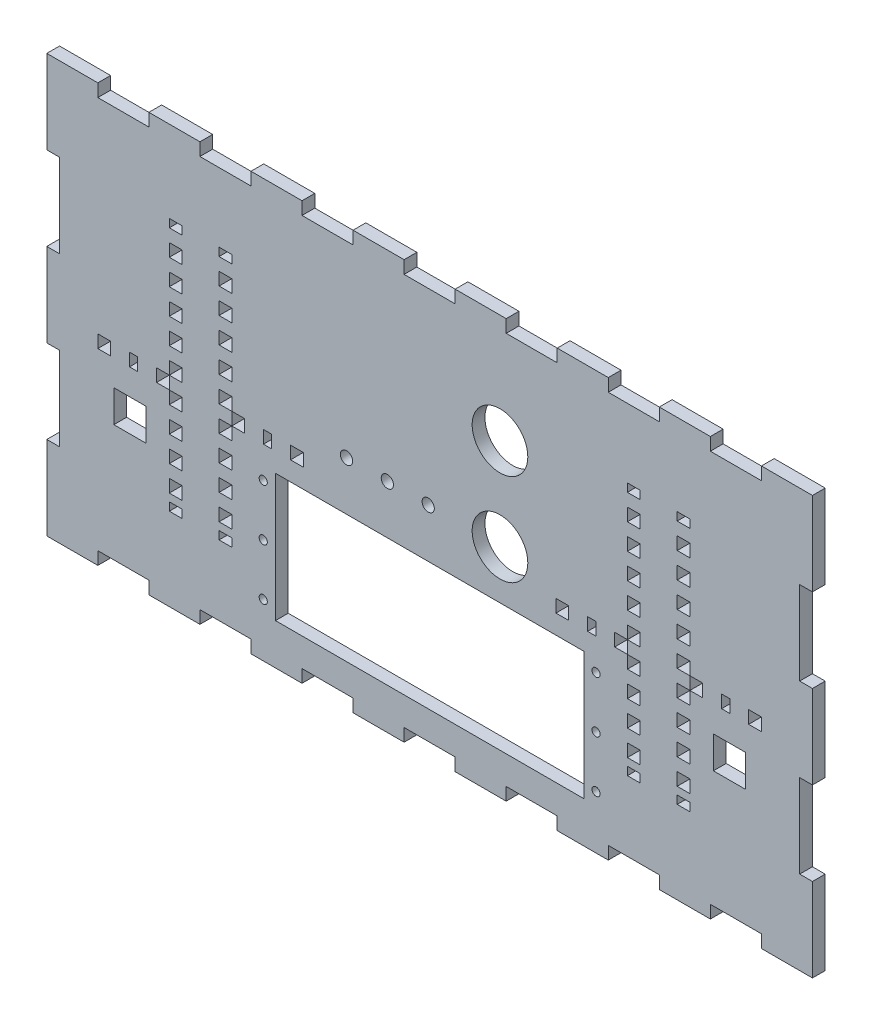
SolidWorks part; units mm, degrees
ref_plane "Front Plane" through (0, 0, 0) normal (0, 0, 1) x (1, 0, 0)
ref_plane "Top Plane" through (0, 0, 0) normal (0, 1, 0) x (1, 0, 0)
ref_plane "Right Plane" through (0, 0, 0) normal (1, 0, 0) x (0, 0, -1)
sketch "Sketch1" plane through (0, 0, 0) normal (0, 0, 1) x (1, 0, 0)
  line B0 (-76.708, -20.066) -> (76.708, -20.066)
  line B1 (76.708, -20.066) -> (76.708, -83.566)
  line B2 (-76.708, -83.566) -> (76.708, -83.566)
  line B3 (-76.708, -20.066) -> (-76.708, -83.566)
  line B4 (158.75, -4.191) -> (158.75, -10.541)
  line B5 (158.75, -4.191) -> (165.1, -4.191)
  line B6 (165.1, -4.191) -> (165.1, -10.541)
  line B7 (158.75, -10.541) -> (165.1, -10.541)
  line B8 (-158.75, -4.191) -> (-165.1, -4.191)
  line B9 (-158.75, -4.191) -> (-158.75, -10.541)
  line B10 (-158.75, -10.541) -> (-165.1, -10.541)
  line B11 (-165.1, -4.191) -> (-165.1, -10.541)
  line B12 (-123.19, 14.8272) -> (-123.19, 8.4772)
  line B13 (-123.19, 8.4772) -> (-129.54, 8.4772)
  line B14 (-129.54, 14.8272) -> (-129.54, 8.4772)
  line B15 (-123.19, 14.8272) -> (-129.54, 14.8272)
  line B16 (-123.19, 27.5273) -> (-123.19, 21.1773)
  line B17 (-123.19, 21.1773) -> (-129.54, 21.1773)
  line B18 (-129.54, 27.5273) -> (-129.54, 21.1773)
  line B19 (-123.19, 27.5273) -> (-129.54, 27.5273)
  line B20 (-123.19, 40.2272) -> (-123.19, 33.8772)
  line B21 (-123.19, 33.8772) -> (-129.54, 33.8772)
  line B22 (-129.54, 40.2272) -> (-129.54, 33.8772)
  line B23 (-123.19, 40.2272) -> (-129.54, 40.2272)
  line B24 (-145.288, -4.191) -> (-149.352, -4.191)
  line B25 (-145.288, -4.191) -> (-145.288, -10.541)
  line B26 (-145.288, -10.541) -> (-149.352, -10.541)
  line B27 (-149.352, -4.191) -> (-149.352, -10.541)
  line B28 (-123.19, -4.2227) -> (-129.54, -4.2227)
  line B29 (-129.54, -4.2227) -> (-129.54, -10.541)
  line B30 (-129.54, -10.541) -> (-135.89, -10.541)
  line B31 (-135.89, -10.541) -> (-135.89, -4.191)
  line B32 (-129.54, -4.191) -> (-135.89, -4.191)
  line B33 (-129.54, 2.1272) -> (-129.54, -4.191)
  line B34 (-123.19, 2.1272) -> (-129.54, 2.1272)
  line B35 (-123.19, 2.1272) -> (-123.19, -4.2227)
  line B36 (-123.19, -10.5728) -> (-129.54, -10.5728)
  line B37 (-123.19, -10.5728) -> (-123.19, -16.9228)
  line B38 (-123.19, -16.9228) -> (-129.54, -16.9228)
  line B39 (-129.54, -10.5728) -> (-129.54, -16.9228)
  line B40 (-123.19, -23.2727) -> (-123.19, -29.6228)
  line B41 (-123.19, -29.6228) -> (-129.54, -29.6228)
  line B42 (-129.54, -23.2727) -> (-129.54, -29.6228)
  line B43 (-123.19, -23.2727) -> (-129.54, -23.2727)
  line B44 (-123.19, -35.9727) -> (-123.19, -42.3227)
  line B45 (-123.19, -42.3227) -> (-129.54, -42.3227)
  line B46 (-129.54, -35.9727) -> (-129.54, -42.3227)
  line B47 (-123.19, -35.9727) -> (-129.54, -35.9727)
  line B48 (-123.19, -48.6728) -> (-123.19, -55.0227)
  line B49 (-123.19, -55.0227) -> (-129.54, -55.0227)
  line B50 (-129.54, -48.6728) -> (-129.54, -55.0227)
  line B51 (-123.19, -48.6728) -> (-129.54, -48.6728)
  line B52 (-123.19, -58.7692) -> (-123.19, -62.8332)
  line B53 (-123.19, -62.8332) -> (-129.54, -62.8332)
  line B54 (-129.54, -58.7692) -> (-129.54, -62.8332)
  line B55 (-123.19, -58.7692) -> (-129.54, -58.7692)
  line B56 (-123.19, 52.9273) -> (-123.19, 46.5772)
  line B57 (-123.19, 46.5772) -> (-129.54, 46.5772)
  line B58 (-129.54, 52.9273) -> (-129.54, 46.5772)
  line B59 (-123.19, 52.9273) -> (-129.54, 52.9273)
  line B60 (-123.19, 63.3412) -> (-129.54, 63.3412)
  line B61 (-123.19, 63.3412) -> (-123.19, 59.2773)
  line B62 (-123.19, 59.2773) -> (-129.54, 59.2773)
  line B63 (-129.54, 63.3412) -> (-129.54, 59.2773)
  line B64 (-104.775, 63.3412) -> (-98.425, 63.3412)
  line B65 (-98.425, 63.3412) -> (-98.425, 59.2773)
  line B66 (-104.775, 59.2773) -> (-98.425, 59.2773)
  line B67 (-104.775, 63.3412) -> (-104.775, 59.2773)
  line B68 (104.775, 2.1272) -> (104.775, -4.2227)
  line B69 (104.775, -4.2227) -> (98.425, -4.2227)
  line B70 (98.425, -4.2227) -> (98.425, -10.541)
  line B71 (98.425, -10.541) -> (92.075, -10.541)
  line B72 (92.075, -10.541) -> (92.075, -4.191)
  line B73 (98.425, -4.191) -> (92.075, -4.191)
  line B74 (98.425, 2.1272) -> (98.425, -4.191)
  line B75 (104.775, 2.1272) -> (98.425, 2.1272)
  line B76 (82.677, -4.191) -> (82.677, -10.541)
  line B77 (82.677, -10.541) -> (78.613, -10.541)
  line B78 (78.613, -4.191) -> (78.613, -10.541)
  line B79 (82.677, -4.191) -> (78.613, -4.191)
  line B80 (62.865, -4.191) -> (62.865, -10.541)
  line B81 (62.865, -4.191) -> (69.215, -4.191)
  line B82 (69.215, -4.191) -> (69.215, -10.541)
  line B83 (62.865, -10.541) -> (69.215, -10.541)
  line B84 (104.775, 14.8272) -> (104.775, 8.4772)
  line B85 (104.775, 8.4772) -> (98.425, 8.4772)
  line B86 (98.425, 14.8272) -> (98.425, 8.4772)
  line B87 (104.775, 14.8272) -> (98.425, 14.8272)
  line B88 (104.775, -10.5728) -> (104.775, -16.9228)
  line B89 (104.775, -16.9228) -> (98.425, -16.9228)
  line B90 (98.425, -10.5728) -> (98.425, -16.9228)
  line B91 (104.775, -10.5728) -> (98.425, -10.5728)
  line B92 (104.775, -23.2727) -> (104.775, -29.6228)
  line B93 (104.775, -29.6228) -> (98.425, -29.6228)
  line B94 (98.425, -23.2727) -> (98.425, -29.6228)
  line B95 (104.775, -23.2727) -> (98.425, -23.2727)
  line B96 (104.775, -35.9727) -> (104.775, -42.3227)
  line B97 (104.775, -42.3227) -> (98.425, -42.3227)
  line B98 (98.425, -35.9727) -> (98.425, -42.3227)
  line B99 (104.775, -35.9727) -> (98.425, -35.9727)
  line B100 (104.775, -48.6728) -> (104.775, -55.0227)
  line B101 (104.775, -55.0227) -> (98.425, -55.0227)
  line B102 (98.425, -48.6728) -> (98.425, -55.0227)
  line B103 (104.775, -48.6728) -> (98.425, -48.6728)
  line B104 (104.775, -58.7692) -> (104.775, -62.8332)
  line B105 (104.775, -62.8332) -> (98.425, -62.8332)
  line B106 (98.425, -58.7692) -> (98.425, -62.8332)
  line B107 (104.775, -58.7692) -> (98.425, -58.7692)
  line B108 (123.19, -10.5728) -> (123.19, -16.9228)
  line B109 (123.19, -10.5728) -> (129.54, -10.5728)
  line B110 (129.54, -10.5728) -> (129.54, -16.9228)
  line B111 (123.19, -16.9228) -> (129.54, -16.9228)
  line B112 (145.288, -4.191) -> (145.288, -10.541)
  line B113 (145.288, -4.191) -> (149.352, -4.191)
  line B114 (149.352, -4.191) -> (149.352, -10.541)
  line B115 (145.288, -10.541) -> (149.352, -10.541)
  line B116 (-62.865, -4.191) -> (-69.215, -4.191)
  line B117 (-62.865, -4.191) -> (-62.865, -10.541)
  line B118 (-62.865, -10.541) -> (-69.215, -10.541)
  line B119 (-69.215, -4.191) -> (-69.215, -10.541)
  line B120 (123.19, 63.3412) -> (123.19, 59.2773)
  line B121 (123.19, 63.3412) -> (129.54, 63.3412)
  line B122 (129.54, 63.3412) -> (129.54, 59.2773)
  line B123 (123.19, 59.2773) -> (129.54, 59.2773)
  line B124 (104.775, 27.5273) -> (104.775, 21.1773)
  line B125 (104.775, 21.1773) -> (98.425, 21.1773)
  line B126 (98.425, 27.5273) -> (98.425, 21.1773)
  line B127 (104.775, 27.5273) -> (98.425, 27.5273)
  line B128 (104.775, 40.2272) -> (104.775, 33.8772)
  line B129 (104.775, 33.8772) -> (98.425, 33.8772)
  line B130 (98.425, 40.2272) -> (98.425, 33.8772)
  line B131 (104.775, 40.2272) -> (98.425, 40.2272)
  line B132 (104.775, 52.9273) -> (104.775, 46.5772)
  line B133 (104.775, 46.5772) -> (98.425, 46.5772)
  line B134 (98.425, 52.9273) -> (98.425, 46.5772)
  line B135 (104.775, 52.9273) -> (98.425, 52.9273)
  line B136 (-190.5, -103.9813) -> (-190.5, 103.9813)
  line B137 (190.5, -103.9813) -> (-190.5, -103.9813)
  line B138 (190.5, 103.9813) -> (190.5, -103.9813)
  line B139 (-190.5, 103.9813) -> (190.5, 103.9813)
  line B140 (104.775, 63.3412) -> (98.425, 63.3412)
  line B141 (104.775, 63.3412) -> (104.775, 59.2773)
  line B142 (104.775, 59.2773) -> (98.425, 59.2773)
  line B143 (98.425, 63.3412) -> (98.425, 59.2773)
  line B144 (123.19, 52.9273) -> (123.19, 46.5772)
  line B145 (123.19, 52.9273) -> (129.54, 52.9273)
  line B146 (129.54, 52.9273) -> (129.54, 46.5772)
  line B147 (123.19, 46.5772) -> (129.54, 46.5772)
  line B148 (123.19, 40.2272) -> (123.19, 33.8772)
  line B149 (123.19, 40.2272) -> (129.54, 40.2272)
  line B150 (129.54, 40.2272) -> (129.54, 33.8772)
  line B151 (123.19, 33.8772) -> (129.54, 33.8772)
  line B152 (123.19, 27.5273) -> (123.19, 21.1773)
  line B153 (123.19, 27.5273) -> (129.54, 27.5273)
  line B154 (129.54, 27.5273) -> (129.54, 21.1773)
  line B155 (123.19, 21.1773) -> (129.54, 21.1773)
  line B156 (123.19, 14.8272) -> (123.19, 8.4772)
  line B157 (123.19, 14.8272) -> (129.54, 14.8272)
  line B158 (129.54, 14.8272) -> (129.54, 8.4772)
  line B159 (123.19, 8.4772) -> (129.54, 8.4772)
  line B160 (-82.677, -4.191) -> (-82.677, -10.541)
  line B161 (-82.677, -4.191) -> (-78.613, -4.191)
  line B162 (-78.613, -4.191) -> (-78.613, -10.541)
  line B163 (-82.677, -10.541) -> (-78.613, -10.541)
  line B164 (-104.775, 2.1272) -> (-104.775, -4.2227)
  line B165 (-104.775, 2.1272) -> (-98.425, 2.1272)
  line B166 (-98.425, 2.1272) -> (-98.425, -4.191)
  line B167 (-98.425, -4.191) -> (-92.075, -4.191)
  line B168 (-92.075, -10.541) -> (-92.075, -4.191)
  line B169 (-98.425, -10.541) -> (-92.075, -10.541)
  line B170 (-98.425, -4.2227) -> (-98.425, -10.541)
  line B171 (-104.775, -4.2227) -> (-98.425, -4.2227)
  line B172 (-104.775, -10.5728) -> (-104.775, -16.9228)
  line B173 (-104.775, -10.5728) -> (-98.425, -10.5728)
  line B174 (-98.425, -10.5728) -> (-98.425, -16.9228)
  line B175 (-104.775, -16.9228) -> (-98.425, -16.9228)
  line B176 (-104.775, -23.2727) -> (-104.775, -29.6228)
  line B177 (-104.775, -23.2727) -> (-98.425, -23.2727)
  line B178 (-98.425, -23.2727) -> (-98.425, -29.6228)
  line B179 (-104.775, -29.6228) -> (-98.425, -29.6228)
  line B180 (-104.775, -35.9727) -> (-104.775, -42.3227)
  line B181 (-104.775, -35.9727) -> (-98.425, -35.9727)
  line B182 (-98.425, -35.9727) -> (-98.425, -42.3227)
  line B183 (-104.775, -42.3227) -> (-98.425, -42.3227)
  line B184 (-104.775, -48.6728) -> (-104.775, -55.0227)
  line B185 (-104.775, -48.6728) -> (-98.425, -48.6728)
  line B186 (-98.425, -48.6728) -> (-98.425, -55.0227)
  line B187 (-104.775, -55.0227) -> (-98.425, -55.0227)
  line B188 (123.19, -4.2227) -> (129.54, -4.2227)
  line B189 (123.19, 2.1272) -> (123.19, -4.2227)
  line B190 (123.19, 2.1272) -> (129.54, 2.1272)
  line B191 (129.54, 2.1272) -> (129.54, -4.191)
  line B192 (129.54, -4.191) -> (135.89, -4.191)
  line B193 (135.89, -10.541) -> (135.89, -4.191)
  line B194 (129.54, -10.541) -> (135.89, -10.541)
  line B195 (129.54, -4.2227) -> (129.54, -10.541)
  line B196 (123.19, -23.2727) -> (123.19, -29.6228)
  line B197 (123.19, -23.2727) -> (129.54, -23.2727)
  line B198 (129.54, -23.2727) -> (129.54, -29.6228)
  line B199 (123.19, -29.6228) -> (129.54, -29.6228)
  line B200 (123.19, -35.9727) -> (123.19, -42.3227)
  line B201 (123.19, -35.9727) -> (129.54, -35.9727)
  line B202 (129.54, -35.9727) -> (129.54, -42.3227)
  line B203 (123.19, -42.3227) -> (129.54, -42.3227)
  line B204 (123.19, -48.6728) -> (123.19, -55.0227)
  line B205 (123.19, -48.6728) -> (129.54, -48.6728)
  line B206 (129.54, -48.6728) -> (129.54, -55.0227)
  line B207 (123.19, -55.0227) -> (129.54, -55.0227)
  line B208 (123.19, -58.7692) -> (123.19, -62.8332)
  line B209 (123.19, -58.7692) -> (129.54, -58.7692)
  line B210 (129.54, -58.7692) -> (129.54, -62.8332)
  line B211 (123.19, -62.8332) -> (129.54, -62.8332)
  line B212 (-104.775, -58.7692) -> (-104.775, -62.8332)
  line B213 (-104.775, -58.7692) -> (-98.425, -58.7692)
  line B214 (-98.425, -58.7692) -> (-98.425, -62.8332)
  line B215 (-104.775, -62.8332) -> (-98.425, -62.8332)
  line B216 (-104.775, 52.9273) -> (-104.775, 46.5772)
  line B217 (-104.775, 52.9273) -> (-98.425, 52.9273)
  line B218 (-98.425, 52.9273) -> (-98.425, 46.5772)
  line B219 (-104.775, 46.5772) -> (-98.425, 46.5772)
  line B220 (-104.775, 40.2272) -> (-104.775, 33.8772)
  line B221 (-104.775, 40.2272) -> (-98.425, 40.2272)
  line B222 (-98.425, 40.2272) -> (-98.425, 33.8772)
  line B223 (-104.775, 33.8772) -> (-98.425, 33.8772)
  line B224 (-104.775, 27.5273) -> (-104.775, 21.1773)
  line B225 (-104.775, 27.5273) -> (-98.425, 27.5273)
  line B226 (-98.425, 27.5273) -> (-98.425, 21.1773)
  line B227 (-104.775, 21.1773) -> (-98.425, 21.1773)
  line B228 (-104.775, 14.8272) -> (-104.775, 8.4772)
  line B229 (-104.775, 14.8272) -> (-98.425, 14.8272)
  line B230 (-98.425, 14.8272) -> (-98.425, 8.4772)
  line B231 (-104.775, 8.4772) -> (-98.425, 8.4772)
  circle B232 centre (-41.3512, 4.2516) radius 3.048
  circle B233 centre (-21.0312, 4.2516) radius 3.048
  circle B234 centre (-0.7112, 4.2516) radius 3.048
  circle B235 centre (35.0145, 4.0644) radius 13.843
  circle B236 centre (35.0145, 49.7844) radius 13.843
  circle B237 centre (-82.804, -51.816) radius 2.032
  circle B238 centre (82.804, -51.816) radius 2.032
  circle B239 centre (-82.804, -26.162) radius 2.032
  circle B240 centre (82.804, -26.162) radius 2.032
  circle B241 centre (82.804, -77.47) radius 2.032
  circle B242 centre (-82.804, -77.47) radius 2.032
sketch_block_instance "Block1-1"
sketch_block "Block1"
sketch "Sketch2" plane through (0, 0, 0) normal (0, 0, 1) x (1, 0, 0)
  line L0 (-190.5, 103.9813) -> (190.5, 103.9813) construction
  line L1 (-165.1, 103.9813) -> (-139.7, 103.9813)
  line L2 (-165.1, 103.9813) -> (-165.1, 97.6313)
  line L3 (-165.1, 97.6313) -> (-139.7, 97.6313)
  line L4 (-139.7, 103.9813) -> (-139.7, 97.6313)
  line L5 (-114.3, 103.9813) -> (-114.3, 97.6313)
  line L6 (-114.3, 103.9813) -> (-88.9, 103.9813)
  line L7 (-88.9, 103.9813) -> (-88.9, 97.6313)
  line L8 (-114.3, 97.6313) -> (-88.9, 97.6313)
  line L9 (-63.5, 103.9813) -> (-63.5, 97.6313)
  line L10 (-63.5, 103.9813) -> (-38.1, 103.9813)
  line L11 (-38.1, 103.9813) -> (-38.1, 97.6313)
  line L12 (-63.5, 97.6313) -> (-38.1, 97.6313)
  line L13 (-12.7, 103.9813) -> (-12.7, 97.6313)
  line L14 (-12.7, 103.9813) -> (12.7, 103.9813)
  line L15 (12.7, 103.9813) -> (12.7, 97.6313)
  line L16 (-12.7, 97.6313) -> (12.7, 97.6313)
  line L17 (38.1, 103.9813) -> (38.1, 97.6313)
  line L18 (38.1, 103.9813) -> (63.5, 103.9813)
  line L19 (63.5, 103.9813) -> (63.5, 97.6313)
  line L20 (38.1, 97.6313) -> (63.5, 97.6313)
  line L21 (88.9, 103.9813) -> (88.9, 97.6313)
  line L22 (88.9, 103.9813) -> (114.3, 103.9813)
  line L23 (114.3, 103.9813) -> (114.3, 97.6313)
  line L24 (88.9, 97.6313) -> (114.3, 97.6313)
  line L25 (139.7, 103.9813) -> (139.7, 97.6313)
  line L26 (139.7, 103.9813) -> (165.1, 103.9813)
  line L27 (165.1, 103.9813) -> (165.1, 97.6313)
  line L28 (139.7, 97.6313) -> (165.1, 97.6313)
  line L29 (-190.5, -103.9813) -> (-190.5, 103.9813) construction
  line L30 (-190.5, 62.3888) -> (-184.15, 62.3888)
  line L31 (-190.5, 62.3888) -> (-190.5, 20.7963)
  line L32 (-190.5, 20.7963) -> (-184.15, 20.7963)
  line L33 (-184.15, 62.3888) -> (-184.15, 20.7963)
  line L34 (-190.5, -20.7962) -> (-190.5, -62.3887)
  line L35 (-190.5, -20.7962) -> (-184.15, -20.7962)
  line L36 (-184.15, -20.7962) -> (-184.15, -62.3887)
  line L37 (-190.5, -62.3887) -> (-184.15, -62.3887)
  line L38 (0, 0) -> (-16.3405, 0)
  line L39 (0, 0) -> (0, -11.515)
  line L40 (139.7, -103.9813) -> (165.1, -103.9813)
  line L41 (165.1, -103.9813) -> (165.1, -97.6313)
  line L42 (139.7, -97.6313) -> (165.1, -97.6313)
  line L43 (139.7, -103.9813) -> (139.7, -97.6313)
  line L44 (88.9, -103.9813) -> (114.3, -103.9813)
  line L45 (114.3, -103.9813) -> (114.3, -97.6313)
  line L46 (88.9, -97.6313) -> (114.3, -97.6313)
  line L47 (88.9, -103.9813) -> (88.9, -97.6313)
  line L48 (38.1, -103.9813) -> (63.5, -103.9813)
  line L49 (63.5, -103.9813) -> (63.5, -97.6313)
  line L50 (38.1, -97.6313) -> (63.5, -97.6313)
  line L51 (38.1, -103.9813) -> (38.1, -97.6313)
  line L52 (-12.7, -103.9813) -> (12.7, -103.9813)
  line L53 (12.7, -103.9813) -> (12.7, -97.6313)
  line L54 (-12.7, -97.6313) -> (12.7, -97.6313)
  line L55 (-12.7, -103.9813) -> (-12.7, -97.6313)
  line L56 (-63.5, -103.9813) -> (-38.1, -103.9813)
  line L57 (-38.1, -103.9813) -> (-38.1, -97.6313)
  line L58 (-63.5, -97.6313) -> (-38.1, -97.6313)
  line L59 (-63.5, -103.9813) -> (-63.5, -97.6313)
  line L60 (-114.3, -103.9813) -> (-88.9, -103.9813)
  line L61 (-88.9, -103.9813) -> (-88.9, -97.6313)
  line L62 (-114.3, -97.6313) -> (-88.9, -97.6313)
  line L63 (-114.3, -103.9813) -> (-114.3, -97.6313)
  line L64 (-165.1, -97.6313) -> (-139.7, -97.6313)
  line L65 (-139.7, -103.9813) -> (-139.7, -97.6313)
  line L66 (-165.1, -103.9813) -> (-139.7, -103.9813)
  line L67 (-165.1, -103.9813) -> (-165.1, -97.6313)
  line L68 (190.5, -20.7962) -> (184.15, -20.7962)
  line L69 (184.15, -20.7962) -> (184.15, -62.3887)
  line L70 (190.5, -62.3887) -> (184.15, -62.3887)
  line L71 (190.5, -20.7962) -> (190.5, -62.3887)
  line L72 (190.5, 20.7963) -> (184.15, 20.7963)
  line L73 (184.15, 62.3888) -> (184.15, 20.7963)
  line L74 (190.5, 62.3888) -> (184.15, 62.3888)
  line L75 (190.5, 62.3888) -> (190.5, 20.7963)
  dimension "D1" = 25.4
  dimension "D2" = 6.35
  dimension "D3" = 25.4
  dimension "D5" = 41.5925
  dimension "D6" = 6.35
  dimension "D7" = 41.5925
  dimension "D4" = 7
  dimension "D8" = 2
extrude "Boss-Extrude1" add sketch "Sketch1" along normal blind 6.35
extrude "Cut-Extrude2" cut sketch "Sketch2" along normal blind 6.35 contours L4 L1 L2 L3 | L5 L8 L7 L6 | L9 L12 L11 L10 | L13 L16 L15 L14 | L17 L20 L19 L18 | L25 L28 L27 L26 | L21 L24 L23 L22 | L75 L74 L73 L72 | L71 L68 L69 L70 | L43 L40 L41 L42 | L51 L48 L49 L50 | L55 L52 L53 L54 | L59 L56 L57 L58 | L63 L60 L61 L62 | L67 L66 L65 L64 | L34 L37 L36 L35 | L33 L30 L31 L32 | L46 L45 L44 L47
sketch "Sketch3" plane through (0, 0, 6.35) normal (0, 0, 1) x (1, 0, 0)
  line L0 (0, 0) -> (0, -42.2402)
  line L1 (-157.1328, -23.4154) -> (-141.2055, -23.4154)
  line L2 (-157.1328, -23.4154) -> (-157.1328, -39.3427)
  line L3 (-157.1328, -39.3427) -> (-141.2055, -39.3427)
  line L4 (-141.2055, -23.4154) -> (-141.2055, -39.3427)
  line L5 (157.1328, -39.3427) -> (141.2055, -39.3427)
  line L6 (141.2055, -23.4154) -> (141.2055, -39.3427)
  line L7 (157.1328, -23.4154) -> (141.2055, -23.4154)
  line L8 (157.1328, -23.4154) -> (157.1328, -39.3427)
extrude "Cut-Extrude3" cut sketch "Sketch3" against normal blind 6.35 contours L4 L1 L2 L3 | L8 L7 L6 L5
